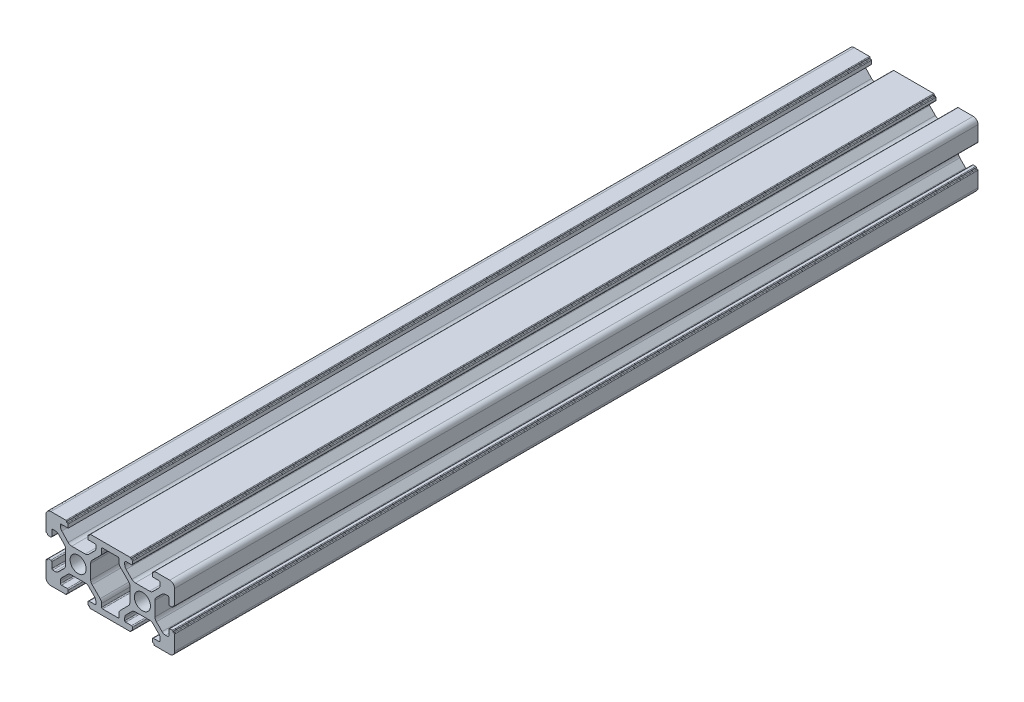
SolidWorks part; units mm, degrees
material "6063-T5"
ref_plane "Front Plane" through (0, 0, 0) normal (0, 0, 1) x (1, 0, 0)
ref_plane "Top Plane" through (0, 0, 0) normal (0, 1, 0) x (1, 0, 0)
ref_plane "Right Plane" through (0, 0, 0) normal (1, 0, 0) x (0, 0, -1)
sketch "Sketch1" plane through (0, 0, 0) normal (0, 0, 1) x (1, 0, 0)
  line L0 (1.5, 0) -> (6.2, 0)
  line L1 (40, 1.5) -> (40, 6.2)
  line L2 (38.5, 20) -> (33.8, 20)
  line L3 (0, 18.5) -> (0, 13.8)
  line L4 (17.6, 1.8) -> (22.4, 1.8)
  line L5 (32.218, 13.9) -> (27.782, 13.9)
  line L6 (26.1, 12.218) -> (26.1, 7.782)
  line L7 (17.6, 18.2) -> (22.4, 18.2)
  line L8 (12.218, 13.9) -> (7.9864, 13.9)
  line L9 (6.1, 12.218) -> (6.1, 7.782)
  line L10 (7.782, 6.1) -> (12.218, 6.1)
  line L11 (13.9, 7.782) -> (13.9, 12.218)
  line L12 (27.782, 6.1) -> (32.218, 6.1)
  line L13 (33.9, 7.782) -> (33.9, 12.218)
  line L14 (26.7213, 14.3393) -> (24.9393, 16.1213)
  line L15 (33.2787, 14.3393) -> (35.0607, 16.1213)
  line L16 (34.3393, 13.2787) -> (36.1213, 15.0607)
  line L17 (25.6607, 6.7213) -> (23.1393, 4.2)
  line L18 (15.2, 1.8) -> (13.4, 1.8)
  line L19 (26.7213, 5.6607) -> (24.9393, 3.8787)
  line L20 (24.8, 1.8) -> (26.6, 1.8)
  line L21 (15.3, 18.2) -> (13.1, 18.2)
  line L22 (13.2787, 14.3393) -> (15.1607, 16.2213)
  line L23 (14.3393, 13.2787) -> (16.8607, 15.8)
  line L24 (5.6607, 6.7213) -> (3.8787, 4.9393)
  line L25 (6.7213, 5.6607) -> (4.9393, 3.8787)
  line L26 (6.897, 14.3689) -> (4.9106, 16.4674)
  line L27 (5.6607, 13.2787) -> (3.8787, 15.0607)
  line L28 (14.3393, 6.7213) -> (16.8607, 4.2)
  line L29 (13.2787, 5.6607) -> (15.0607, 3.8787)
  line L30 (24.8, 18.2) -> (26.6, 18.2)
  line L31 (25.6607, 13.2787) -> (23.1393, 15.8)
  line L32 (34.3393, 6.7213) -> (36.1213, 4.9393)
  line L33 (33.2787, 5.6607) -> (35.0607, 3.8787)
  line L34 (1.8, 15.2) -> (1.8, 13.4)
  line L35 (24.5, 2.1) -> (24.5, 2.818)
  line L36 (4.5, 2.1) -> (4.5, 2.818)
  line L37 (2.818, 4.5) -> (2.1, 4.5)
  line L38 (4.5, 17.9) -> (4.5, 17.4986)
  line L39 (2.818, 15.5) -> (2.1, 15.5)
  line L40 (15.6, 17.9) -> (15.6, 17.282)
  line L41 (15.5, 2.818) -> (15.5, 2.1)
  line L42 (38.2, 15.2) -> (38.2, 13.4)
  line L43 (35.5, 2.818) -> (35.5, 2.1)
  line L44 (37.182, 4.5) -> (37.9, 4.5)
  line L45 (35.5, 17.182) -> (35.5, 17.9)
  line L46 (37.182, 15.5) -> (37.9, 15.5)
  line L47 (17.3, 2.1) -> (17.3, 3.1393)
  line L48 (22.7, 2.1) -> (22.7, 3.1393)
  line L49 (17.3, 17.9) -> (17.3, 16.8607)
  line L50 (22.7, 17.9) -> (22.7, 16.8607)
  line L51 (24.5, 17.9) -> (24.5, 17.182)
  line L52 (6.9, 19.3) -> (6.9, 18.2)
  line L53 (13.1, 19.3) -> (13.1, 18.2)
  line L54 (6.9, 1.5) -> (6.9, 0.7)
  line L55 (13.1, 1.5) -> (13.1, 0.7)
  line L56 (13.8, 0) -> (26.2, 0)
  line L57 (6.6, 1.8) -> (4.8, 1.8)
  line L58 (6.9, 18.2) -> (4.8, 18.2)
  line L59 (6.2, 20) -> (1.5, 20)
  line L60 (39.3, 6.9) -> (38.5, 6.9)
  line L61 (39.3, 13.1) -> (38.5, 13.1)
  line L62 (1.5, 13.1) -> (0.7, 13.1)
  line L63 (1.5, 6.9) -> (0.7, 6.9)
  line L64 (0, 6.2) -> (0, 1.5)
  line L65 (1.8, 6.6) -> (1.8, 4.8)
  line L66 (38.2, 6.6) -> (38.2, 4.8)
  line L67 (40, 13.8) -> (40, 18.5)
  line L68 (33.1, 19.3) -> (33.1, 18.5)
  line L69 (26.9, 19.3) -> (26.9, 18.5)
  line L70 (26.9, 1.5) -> (26.9, 0.7)
  line L71 (33.1, 1.5) -> (33.1, 0.7)
  line L72 (33.8, 0) -> (38.5, 0)
  line L73 (33.4, 1.8) -> (35.2, 1.8)
  line L74 (26.2, 20) -> (13.8, 20)
  line L75 (33.4, 18.2) -> (35.2, 18.2)
  line L76 (6.7, 0.5) -> (6.6, 0.5)
  line L77 (6.4, 0.3) -> (6.4, 0.2)
  line L78 (13.3, 0.5) -> (13.4, 0.5)
  line L79 (13.6, 0.3) -> (13.6, 0.2)
  line L80 (26.7, 0.5) -> (26.6, 0.5)
  line L81 (26.4, 0.3) -> (26.4, 0.2)
  line L82 (33.3, 0.5) -> (33.4, 0.5)
  line L83 (33.6, 0.3) -> (33.6, 0.2)
  line L85 (6.4, 19.8) -> (6.4, 19.7)
  line L86 (6.6, 19.5) -> (6.7, 19.5)
  line L87 (13.6, 19.8) -> (13.6, 19.7)
  line L88 (13.4, 19.5) -> (13.3, 19.5)
  line L89 (26.4, 19.8) -> (26.4, 19.7)
  line L90 (26.6, 19.5) -> (26.7, 19.5)
  line L91 (33.6, 19.8) -> (33.6, 19.7)
  line L92 (33.4, 19.5) -> (33.3, 19.5)
  line L93 (0.5, 13.3) -> (0.5, 13.4)
  line L94 (0.3, 13.6) -> (0.2, 13.6)
  line L95 (0.5, 6.7) -> (0.5, 6.6)
  line L96 (0.3, 6.4) -> (0.2, 6.4)
  line L97 (39.5, 13.3) -> (39.5, 13.4)
  line L98 (39.7, 13.6) -> (39.8, 13.6)
  line L99 (39.5, 6.7) -> (39.5, 6.6)
  line L100 (39.7, 6.4) -> (39.8, 6.4)
  circle A0 centre (10, 10) radius 2.5
  circle A1 centre (30, 10) radius 2.5
  arc A2 (38.5, 0) -> (40, 1.5) centre (38.5, 1.5) ccw
  arc A3 (40, 18.5) -> (38.5, 20) centre (38.5, 18.5) ccw
  arc A4 (1.5, 0) -> (0, 1.5) centre (1.5, 1.5) cw
  arc A5 (1.5, 20) -> (0, 18.5) centre (1.5, 18.5) ccw
  arc A6 (26.7213, 5.6607) -> (27.782, 6.1) centre (27.782, 4.6) cw
  arc A7 (32.218, 6.1) -> (33.2787, 5.6607) centre (32.218, 4.6) cw
  arc A8 (33.9, 7.782) -> (34.3393, 6.7213) centre (35.4, 7.782) ccw
  arc A9 (33.2787, 14.3393) -> (32.218, 13.9) centre (32.218, 15.4) cw
  arc A10 (14.3393, 6.7213) -> (13.9, 7.782) centre (15.4, 7.782) cw
  arc A11 (14.3393, 13.2787) -> (13.9, 12.218) centre (15.4, 12.218) ccw
  arc A12 (25.6607, 6.7213) -> (26.1, 7.782) centre (24.6, 7.782) ccw
  arc A13 (26.1, 12.218) -> (25.6607, 13.2787) centre (24.6, 12.218) ccw
  arc A14 (27.782, 13.9) -> (26.7213, 14.3393) centre (27.782, 15.4) cw
  arc A15 (5.6607, 13.2787) -> (6.1, 12.218) centre (4.6, 12.218) cw
  arc A16 (5.6607, 6.7213) -> (6.1, 7.782) centre (4.6, 7.782) ccw
  arc A17 (13.2787, 5.6607) -> (12.218, 6.1) centre (12.218, 4.6) ccw
  arc A18 (6.7213, 5.6607) -> (7.782, 6.1) centre (7.782, 4.6) cw
  arc A19 (13.2787, 14.3393) -> (12.218, 13.9) centre (12.218, 15.4) cw
  arc A20 (6.897, 14.3689) -> (7.9864, 13.9) centre (7.9864, 15.4) ccw
  arc A21 (36.1213, 4.9393) -> (37.182, 4.5) centre (37.182, 6) ccw
  arc A22 (36.1213, 15.0607) -> (37.182, 15.5) centre (37.182, 14) cw
  arc A23 (35.0607, 16.1213) -> (35.5, 17.182) centre (34, 17.182) ccw
  arc A24 (24.5, 17.182) -> (24.9393, 16.1213) centre (26, 17.182) ccw
  arc A25 (22.7, 16.8607) -> (23.1393, 15.8) centre (24.2, 16.8607) ccw
  arc A26 (17.3, 16.8607) -> (16.8607, 15.8) centre (15.8, 16.8607) cw
  arc A27 (4.9106, 16.4674) -> (4.5, 17.4986) centre (6, 17.4986) cw
  arc A28 (15.6, 17.282) -> (15.1607, 16.2213) centre (14.1, 17.282) cw
  arc A29 (3.8787, 15.0607) -> (2.818, 15.5) centre (2.818, 14) ccw
  arc A30 (3.8787, 4.9393) -> (2.818, 4.5) centre (2.818, 6) cw
  arc A31 (4.9393, 3.8787) -> (4.5, 2.818) centre (6, 2.818) ccw
  arc A32 (35.0607, 3.8787) -> (35.5, 2.818) centre (34, 2.818) cw
  arc A33 (24.9393, 3.8787) -> (24.5, 2.818) centre (26, 2.818) ccw
  arc A34 (22.7, 3.1393) -> (23.1393, 4.2) centre (24.2, 3.1393) cw
  arc A35 (17.3, 3.1393) -> (16.8607, 4.2) centre (15.8, 3.1393) ccw
  arc A36 (15.5, 2.818) -> (15.0607, 3.8787) centre (14, 2.818) ccw
  arc A37 (1.8, 6.6) -> (1.5, 6.9) centre (1.5, 6.6) ccw
  arc A38 (1.8, 13.4) -> (1.5, 13.1) centre (1.5, 13.4) cw
  arc A39 (17.6, 18.2) -> (17.3, 17.9) centre (17.6, 17.9) ccw
  arc A40 (22.4, 1.8) -> (22.7, 2.1) centre (22.4, 2.1) ccw
  arc A41 (17.6, 1.8) -> (17.3, 2.1) centre (17.6, 2.1) cw
  arc A42 (15.2, 1.8) -> (15.5, 2.1) centre (15.2, 2.1) ccw
  arc A43 (6.6, 1.8) -> (6.9, 1.5) centre (6.6, 1.5) cw
  arc A44 (13.4, 1.8) -> (13.1, 1.5) centre (13.4, 1.5) ccw
  arc A45 (24.8, 1.8) -> (24.5, 2.1) centre (24.8, 2.1) cw
  arc A46 (35.2, 1.8) -> (35.5, 2.1) centre (35.2, 2.1) ccw
  arc A47 (26.6, 1.8) -> (26.9, 1.5) centre (26.6, 1.5) cw
  arc A48 (33.4, 1.8) -> (33.1, 1.5) centre (33.4, 1.5) ccw
  arc A49 (26.9, 18.5) -> (26.6, 18.2) centre (26.6, 18.5) cw
  arc A50 (33.1, 18.5) -> (33.4, 18.2) centre (33.4, 18.5) ccw
  arc A51 (37.9, 4.5) -> (38.2, 4.8) centre (37.9, 4.8) ccw
  arc A52 (38.5, 13.1) -> (38.2, 13.4) centre (38.5, 13.4) cw
  arc A53 (38.5, 6.9) -> (38.2, 6.6) centre (38.5, 6.6) ccw
  arc A54 (38.2, 15.2) -> (37.9, 15.5) centre (37.9, 15.2) ccw
  arc A55 (35.2, 18.2) -> (35.5, 17.9) centre (35.2, 17.9) cw
  arc A56 (24.8, 18.2) -> (24.5, 17.9) centre (24.8, 17.9) ccw
  arc A57 (22.4, 18.2) -> (22.7, 17.9) centre (22.4, 17.9) cw
  arc A58 (15.3, 18.2) -> (15.6, 17.9) centre (15.3, 17.9) cw
  arc A59 (4.5, 17.9) -> (4.8, 18.2) centre (4.8, 17.9) cw
  arc A60 (1.8, 15.2) -> (2.1, 15.5) centre (2.1, 15.2) cw
  arc A61 (1.8, 4.8) -> (2.1, 4.5) centre (2.1, 4.8) ccw
  arc A62 (4.5, 2.1) -> (4.8, 1.8) centre (4.8, 2.1) ccw
  arc A63 (34.3393, 13.2787) -> (33.9, 12.218) centre (35.4, 12.218) ccw
  arc A64 (6.4, 0.2) -> (6.2, 0) centre (6.2, 0.2) cw
  arc A65 (6.6, 0.5) -> (6.4, 0.3) centre (6.6, 0.3) ccw
  arc A66 (6.7, 0.5) -> (6.9, 0.7) centre (6.7, 0.7) ccw
  arc A67 (13.6, 0.2) -> (13.8, 0) centre (13.8, 0.2) ccw
  arc A68 (13.4, 0.5) -> (13.6, 0.3) centre (13.4, 0.3) cw
  arc A69 (13.3, 0.5) -> (13.1, 0.7) centre (13.3, 0.7) cw
  arc A70 (26.4, 0.2) -> (26.2, 0) centre (26.2, 0.2) cw
  arc A71 (26.6, 0.5) -> (26.4, 0.3) centre (26.6, 0.3) ccw
  arc A72 (26.7, 0.5) -> (26.9, 0.7) centre (26.7, 0.7) ccw
  arc A73 (33.6, 0.2) -> (33.8, 0) centre (33.8, 0.2) ccw
  arc A74 (33.4, 0.5) -> (33.6, 0.3) centre (33.4, 0.3) cw
  arc A75 (33.3, 0.5) -> (33.1, 0.7) centre (33.3, 0.7) cw
  arc A76 (39.8, 6.4) -> (40, 6.2) centre (39.8, 6.2) cw
  arc A77 (39.5, 6.6) -> (39.7, 6.4) centre (39.7, 6.6) ccw
  arc A78 (39.5, 6.7) -> (39.3, 6.9) centre (39.3, 6.7) ccw
  arc A79 (39.5, 13.3) -> (39.3, 13.1) centre (39.3, 13.3) cw
  arc A80 (39.5, 13.4) -> (39.7, 13.6) centre (39.7, 13.4) cw
  arc A81 (39.8, 13.6) -> (40, 13.8) centre (39.8, 13.8) ccw
  arc A82 (33.3, 19.5) -> (33.1, 19.3) centre (33.3, 19.3) ccw
  arc A83 (33.6, 19.7) -> (33.4, 19.5) centre (33.4, 19.7) cw
  arc A84 (33.6, 19.8) -> (33.8, 20) centre (33.8, 19.8) cw
  arc A85 (26.7, 19.5) -> (26.9, 19.3) centre (26.7, 19.3) cw
  arc A86 (26.4, 19.7) -> (26.6, 19.5) centre (26.6, 19.7) ccw
  arc A87 (26.4, 19.8) -> (26.2, 20) centre (26.2, 19.8) ccw
  arc A88 (0.2, 6.4) -> (0, 6.2) centre (0.2, 6.2) ccw
  arc A89 (0.5, 6.6) -> (0.3, 6.4) centre (0.3, 6.6) cw
  arc A90 (0.5, 6.7) -> (0.7, 6.9) centre (0.7, 6.7) cw
  arc A91 (13.3, 19.5) -> (13.1, 19.3) centre (13.3, 19.3) ccw
  arc A92 (13.6, 19.7) -> (13.4, 19.5) centre (13.4, 19.7) cw
  arc A93 (13.6, 19.8) -> (13.8, 20) centre (13.8, 19.8) cw
  arc A94 (6.2, 20) -> (6.4, 19.8) centre (6.2, 19.8) cw
  arc A95 (6.7, 19.5) -> (6.9, 19.3) centre (6.7, 19.3) cw
  arc A96 (6.4, 19.7) -> (6.6, 19.5) centre (6.6, 19.7) ccw
  arc A97 (0.5, 13.3) -> (0.7, 13.1) centre (0.7, 13.3) ccw
  arc A98 (0.2, 13.6) -> (0, 13.8) centre (0.2, 13.8) cw
  arc A99 (0.5, 13.4) -> (0.3, 13.6) centre (0.3, 13.4) ccw
  point P87 (0, 0)
  point P178 (1.8, 6.9)
  point P181 (1.8, 13.1)
  point P186 (22.7, 1.8)
  point P193 (6.9, 1.8)
  point P204 (33.1, 1.8)
  point P209 (33.1, 18.2)
  point P216 (38.2, 6.9)
  point P243 (6.9, 0.5)
  point P248 (13.6, 0.5)
  point P257 (26.9, 0.5)
extrude "Boss-Extrude2" add sketch "Sketch1" along normal blind 250 contours A57 L7 A39 L49 A26 L23 A11 L11 A10 L28 A35 L47 A41 L4 A40 L48 A34 L17 A12 L6 A13 L31 A25 L50 | A0 | A1 | L59 A5 L3 A98 L94 A99 L93 A97 L62 A38 L34 A60 L39 A29 L27 A15 L9 A16 L24 A30 L37 A61 L65 A37 L63 A90 L95 A89 L96 A88 L64 A4 L0 A64 L77 A65 L76 A66 L54 A43 L57 A62 L36 A31 L25 A18 L10 A17 L29 A36 L41 A42 L18 A44 L55 A69 L78 A68 L79 A67 L56 A70 L81 A71 L80 A72 L70 A47 L20 A45 L35 A33 L19 A6 L12 A7 L33 A32 L43 A46 L73 A48 L71 A75 L82 A74 L83 A73 L72 A2 L1 A76 L100 A77 L99 A78 L60 A53 L66 A51 L44 A21 L32 A8 L13 A63 L16 A22 L46 A54 L42 A52 L61 A79 L97 A80 L98 A81 L67 A3 L2 A84 L91 A83 L92 A82 L68 A50 L75 A55 L45 A23 L15 A9 L5 A14 L14 A24 L51 A56 L30 A49 L69 A85 L90 A86 L89 A87 L74 A93 L87 A92 L88 A91 L53 L21 A58 L40 A28 L22 A19 L8 A20 L26 A27 L38 A59 L58 L52 A95 L86 A96 L85 A94
